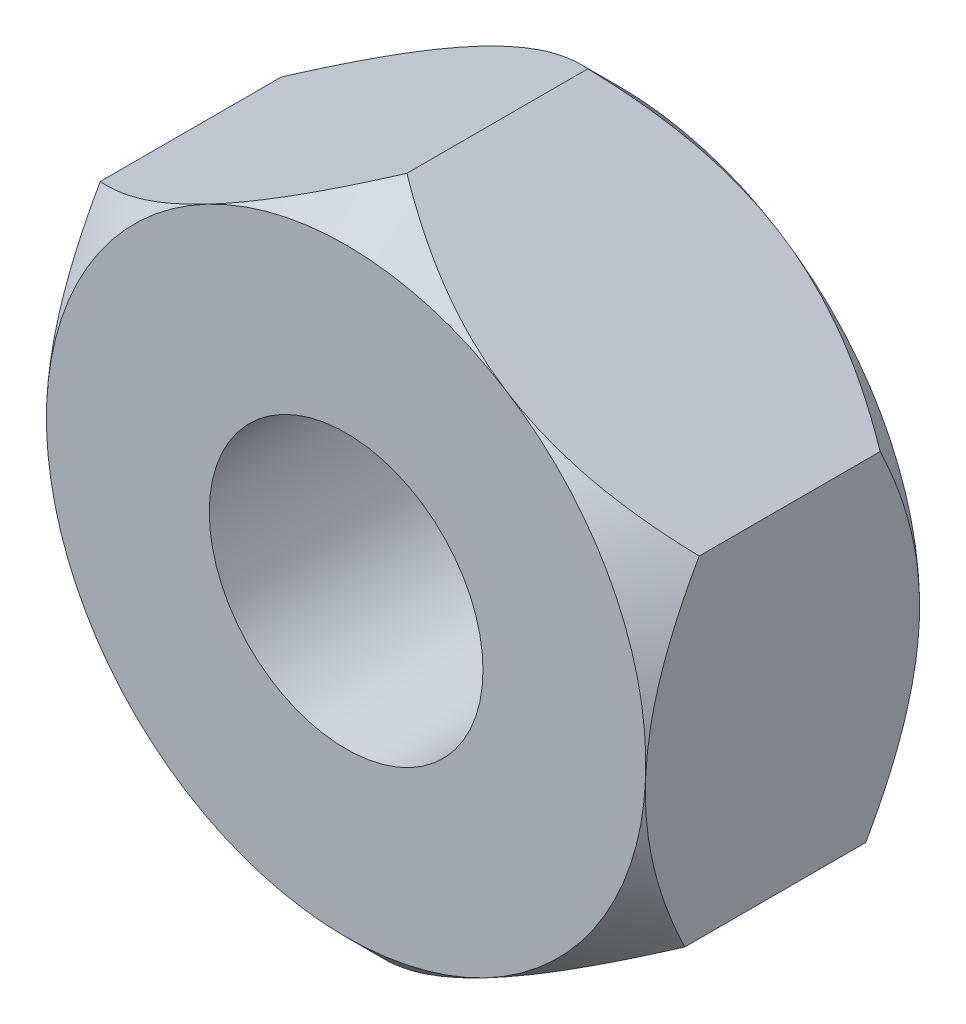
SolidWorks part; units mm, degrees
ref_plane "Front Plane" through (0, 0, 0) normal (0, 0, 1) x (1, 0, 0)
ref_plane "Top Plane" through (0, 0, 0) normal (0, 1, 0) x (1, 0, 0)
ref_plane "Right Plane" through (0, 0, 0) normal (1, 0, 0) x (0, 0, -1)
sketch "Sketch1" plane through (0, 0, 0) normal (0, 0, 1) x (1, 0, 0)
  line L1 (10.1426, -6.4324) -> (10.642, 5.5676)
  line L2 (10.642, 5.5676) -> (0.4993, 12)
  line L3 (0.4993, 12) -> (-10.1426, 6.4324)
  line L4 (-10.1426, 6.4324) -> (-10.642, -5.5676)
  line L5 (-10.642, -5.5676) -> (-0.4993, -12)
  line L6 (-0.4993, -12) -> (10.1426, -6.4324)
  circle A0 centre (0, 0) radius 10.4013 construction
  circle A1 centre (0, 0) radius 4.75
  dimension "D2" = 9.5
  dimension "D1" = 12
extrude "Boss-Extrude1" add sketch "Sketch1" along normal mid plane 9.5
sketch "Sketch2" plane through (0, 0, 4.75) normal (0, 0, 1) x (1, 0, 0)
  line L0 (10.642, 5.5676) -> (0.4993, 12) construction
  circle A0 centre (0, 0) radius 10.4013
extrude "Cut-Extrude1" cut sketch "Sketch2" against normal blind 9.5 draft 45 flip side to cut
mirror "Mirror1" about plane through (0, 0, 0) normal (0, 0, 1) of "Cut-Extrude1"
